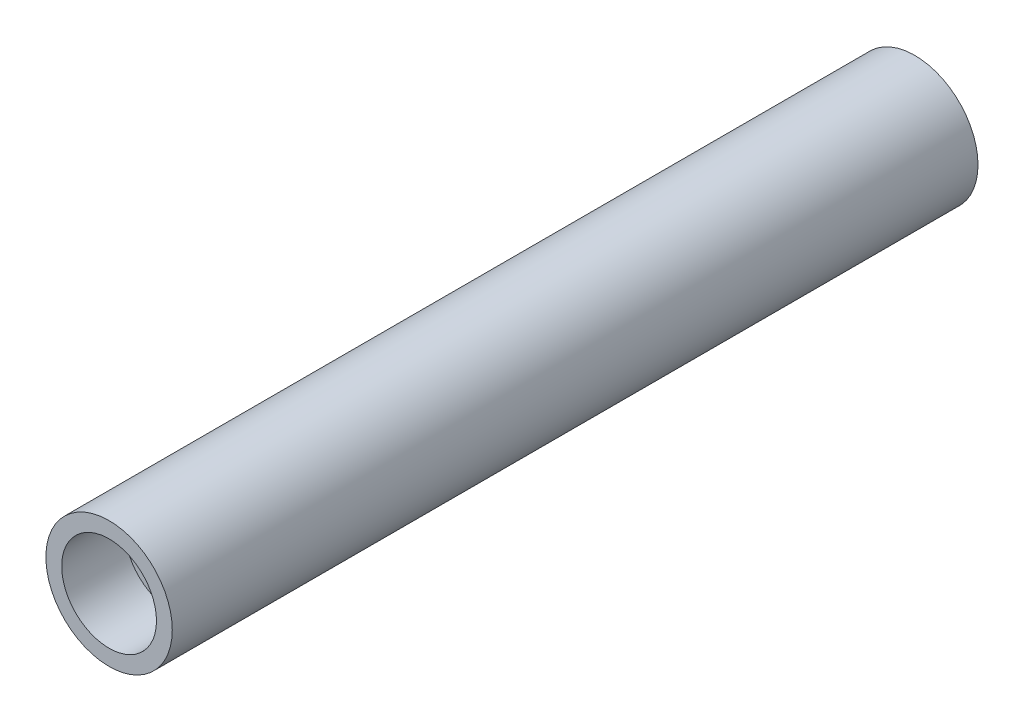
SolidWorks part; units mm, degrees
material "6061-T6 (SS)"
ref_plane "Front Plane" through (0, 0, 0) normal (0, 0, 1) x (1, 0, 0)
ref_plane "Top Plane" through (0, 0, 0) normal (0, 1, 0) x (1, 0, 0)
ref_plane "Right Plane" through (0, 0, 0) normal (1, 0, 0) x (0, 0, -1)
sketch "Sketch1" plane through (0, 0, 0) normal (0, 0, 1) x (1, 0, 0)
  circle A0 centre (0, 0) radius 8
  circle A1 centre (0, 0) radius 3.3
extrude "Frame_Bench_Column" add sketch "Sketch1" along normal blind 102
sketch "Sketch2" plane through (0, 0, 102) normal (0, 0, 1) x (1, 0, 0)
  circle A0 centre (0, 0) radius 6
extrude "Upper_Nut_Clearance_Pocket" cut sketch "Sketch2" against normal blind 8
